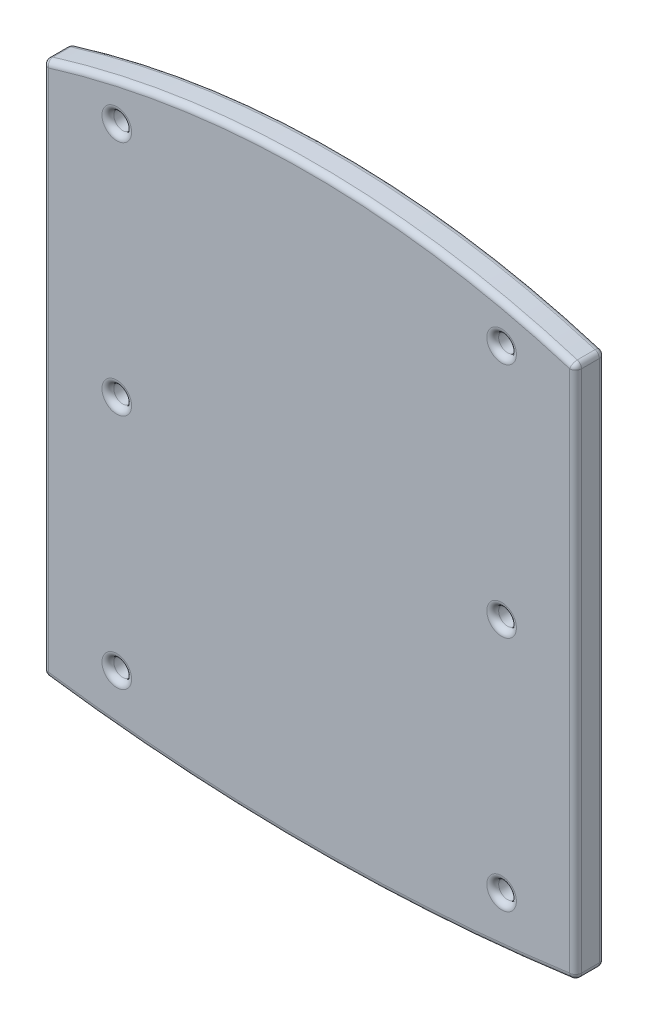
SolidWorks part; units mm, degrees
ref_plane "Front Plane" through (0, 0, 0) normal (0, 0, 1) x (1, 0, 0)
ref_plane "Top Plane" through (0, 0, 0) normal (0, 1, 0) x (1, 0, 0)
ref_plane "Right Plane" through (0, 0, 0) normal (1, 0, 0) x (0, 0, -1)
sketch "Sketch2" plane through (0, 0, 0) normal (0, 0, 1) x (1, 0, 0)
  line L1 (90, 86.2696) -> (-90, 86.2696)
  line L2 (90, 86.2696) -> (90, -93.7304)
  line L3 (90, -93.7304) -> (-90, -93.7304)
  line L4 (-90, 86.2696) -> (-90, -93.7304)
  arc A0 (-90, 86.2696) -> (90, 86.2696) centre (0, -201.8302) cw
  arc A1 (90, -93.7304) -> (-90, -93.7304) centre (0, 549.1136) cw
  point P5 (0, 86.2696)
  point P7 (0, 100)
  point P9 (0, -100)
  dimension "D1" = 180
  dimension "D2" = 180
  dimension "D3" = 0
  dimension "D4" = 100
  dimension "D5" = 100
extrude "Boss-Extrude1" add sketch "Sketch2" along normal blind 10 contours L1 L4 L3 L2 | A0 L1 | A1 L3
sketch "Sketch3" plane through (0, 0, 0) normal (0, 0, 1) x (1, 0, 0)
  line L0 (90, 86.2696) -> (90, -93.7304) construction
  line L1 (90, 70) -> (75, 70)
  line L2 (90, 70) -> (90, 20)
  line L3 (90, 20) -> (75, 20)
  line L4 (75, 70) -> (75, 20)
  point P6 (90, 45)
  dimension "D1" = 50
  dimension "D2" = 15
  dimension "D3" = 45
sketch "Sketch4" plane through (0, 0, 0) normal (0, 0, 1) x (1, 0, 0)
  circle A0 centre (-65, 0) radius 3
  dimension "D1" = 0
  dimension "D2" = 65
extrude "Cut-Extrude4" cut sketch "Sketch4" along normal blind 10
pattern_linear "LPattern2" count 2 spacing 130 along (1, 0, 0) count 2 spacing 80 along (0, -1, 0) of "Cut-Extrude4"
pattern_linear "LPattern3" count 2 spacing 80 along (0, 1, 0) of "LPattern2", "Cut-Extrude4"
fillet "Fillet1" radius 2 24 edges at (-90, -93.7304, 5) (68, -80, 10) (68, -80, 0) (-62, -80, 10) (-62, -80, 0) (0, -100, 0) (0, -100, 10) (-90, -3.7304, 0) (-90, -3.7304, 10) (-62, 0, 10) (-62, 0, 0) (68, 0, 10) (68, 0, 0) (-62, 80, 10) (-62, 80, 0) (68, 80, 10) (68, 80, 0) (90, -93.7304, 5) (90, -3.7304, 0) (90, -3.7304, 10) (90, 86.2696, 5) (0, 100, 0) (0, 100, 10) (-90, 86.2696, 5)
